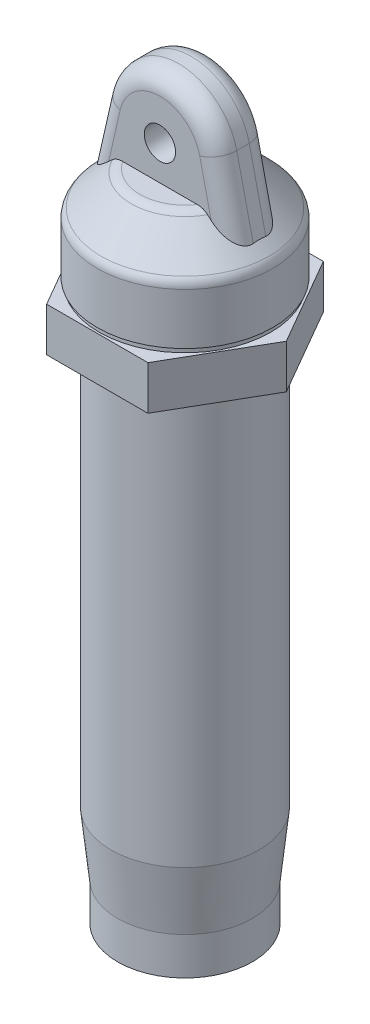
SolidWorks part; units mm, degrees
ref_plane "Front Plane" through (0, 0, 0) normal (0, 0, 1) x (1, 0, 0)
ref_plane "Top Plane" through (0, 0, 0) normal (0, 1, 0) x (1, 0, 0)
ref_plane "Right Plane" through (0, 0, 0) normal (1, 0, 0) x (0, 0, -1)
sketch "Sketch1" plane through (0, 0, 0) normal (0, 1, 0) x (1, 0, 0)
  circle A0 centre (0, 0) radius 5.375
  dimension "D1" = 10.75
extrude "Boss-Extrude1" add sketch "Sketch1" along normal blind 3
sketch "Sketch2" plane through (0, 3, 0) normal (0, 1, 0) x (1, 0, 0)
  circle A0 centre (0, 0) radius 5.375
  circle A1 centre (0, 0) radius 5.375 construction
extrude "Boss-Extrude2" add sketch "Sketch2" along normal blind 5 draft 6 draft outward yes
sketch "Sketch3" plane through (0, 8, 0) normal (0, 1, 0) x (1, 0, 0)
  circle A0 centre (0, 0) radius 5.9005
  circle A1 centre (0, 0) radius 5.9005 construction
extrude "Boss-Extrude3" add sketch "Sketch3" along normal blind 32.75
sketch "Sketch5" plane through (0, 40.75, 0) normal (0, 1, 0) x (1, 0, 0)
  line L1 (-4.0415, 7) -> (-8.0829, 0)
  line L2 (-8.0829, 0) -> (-4.0415, -7)
  line L3 (-4.0415, -7) -> (4.0415, -7)
  line L4 (4.0415, -7) -> (8.0829, 0)
  line L5 (8.0829, 0) -> (4.0415, 7)
  line L6 (4.0415, 7) -> (-4.0415, 7)
  circle A0 centre (0, 0) radius 7 construction
  dimension "D1" = 14
extrude "Boss-Extrude4" add sketch "Sketch5" along normal blind 3.5
sketch "Sketch6" plane through (0, 44.25, 0) normal (0, 1, 0) x (1, 0, 0)
  circle A0 centre (0, 0) radius 6.8468
extrude "Boss-Extrude5" add sketch "Sketch6" along normal blind 0.3969
sketch "Sketch7" plane through (0, 44.6469, 0) normal (0, 1, 0) x (1, 0, 0)
  circle A0 centre (0, 0) radius 7
  dimension "D1" = 14
extrude "Boss-Extrude6" add sketch "Sketch7" along normal blind 4.5
sketch "Sketch8" plane through (0, 49.1469, 0) normal (0, 1, 0) x (1, 0, 0)
  circle A0 centre (0, 0) radius 7
  circle A1 centre (0, 0) radius 7 construction
extrude "Boss-Extrude7" add sketch "Sketch8" along normal blind 3 draft 45
sketch "Sketch9" plane through (0, 0, 0) normal (0, 0, 1) x (1, 0, 0)
  line L0 (4.6316, 55.9507) -> (6.1796, 49.1469)
  line L1 (-4.6316, 55.9507) -> (-6.1796, 49.1469)
  line L2 (-6.1796, 49.1469) -> (6.1796, 49.1469)
  line L3 (0, 49.1469) -> (0, 40.8388) construction
  line L4 (0, 59.6469) -> (4.9173, 59.6469) construction
  line L5 (-6.8468, 44.6469) -> (6.8468, 44.6469) construction
  line L6 (0, 56.1469) -> (2.8337, 56.1469) construction
  line L7 (7, 49.1469) -> (-7, 49.1469) construction
  circle A0 centre (0, 54.8969) radius 1.25
  circle A1 centre (0, 54.8969) radius 4.75
  dimension "D2" = 2.5
  dimension "D1" = 15
  dimension "D3" = 3.5
extrude "Boss-Extrude8" add sketch "Sketch9" along normal blind 2 and the other way blind 2 contours A1 A0 | A1 L1 L2 L0
fillet "Fillet1" radius 1 3 edges at (0, 52.1469, 4) (0, 49.1469, 7) (0, 52.1469, -4)
fillet "Fillet2" radius 1.5 6 edges at (-5.3324, 52.8708, -2) (0, 59.6469, -2) (-5.3324, 52.8708, 2) (0, 59.6469, 2) (5.3324, 52.8708, -2) (5.3324, 52.8708, 2)
sketch "Sketch10" plane through (0, 0, 0) normal (0, -1, 0) x (1, 0, 0)
  circle A0 centre (0, 0) radius 1.5
  dimension "D1" = 3
extrude "Cut-Extrude1" cut sketch "Sketch10" against normal up to surface (44.25 mm away) up to face at (0, 44.25, 6.8468)
